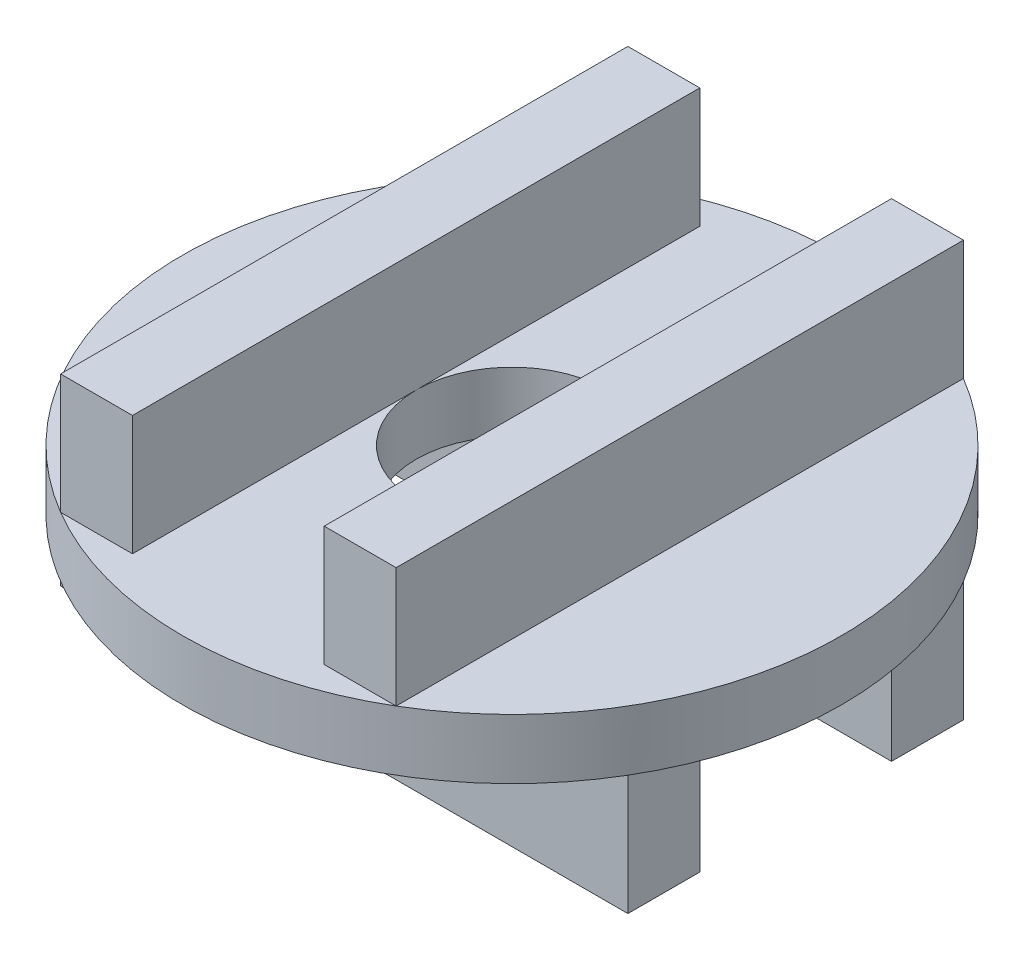
SolidWorks part; units mm, degrees
ref_plane "Front Plane" through (0, 0, 0) normal (0, 0, 1) x (1, 0, 0)
ref_plane "Top Plane" through (0, 0, 0) normal (0, 1, 0) x (1, 0, 0)
ref_plane "Right Plane" through (0, 0, 0) normal (1, 0, 0) x (0, 0, -1)
sketch "Sketch1" plane through (0, 0, 0) normal (0, 1, 0) x (1, 0, 0)
  circle A0 centre (0, 0) radius 55
  circle A1 centre (0, 0) radius 16
  dimension "D1" = 110
  dimension "D2" = 32
extrude "Boss-Extrude1" add sketch "Sketch1" along normal blind 10
sketch "Sketch2" plane through (0, 10, 0) normal (0, 1, 0) x (1, 0, 0)
  line L0 (0, -5.5) -> (0, 5.5) construction
  line L1 (28, 47.3392) -> (16, 47.3392)
  line L2 (28, 47.3392) -> (28, -47.3392)
  line L3 (28, -47.3392) -> (16, -47.3392)
  line L4 (16, 47.3392) -> (16, -47.3392)
  line L5 (-28, -47.3392) -> (-16, -47.3392)
  line L6 (-16, 47.3392) -> (-16, -47.3392)
  line L7 (-28, 47.3392) -> (-16, 47.3392)
  line L8 (-28, 47.3392) -> (-28, -47.3392)
  circle A0 centre (0, 0) radius 55 construction
  circle A1 centre (0, 0) radius 16 construction
  point P6 (0, 0)
  point P7 (0, 0)
  dimension "D1" = 12
extrude "Boss-Extrude2" add sketch "Sketch2" along normal blind 20
sketch "Sketch4" plane through (0, 0, 0) normal (0, -1, 0) x (1, 0, 0)
  line L0 (16.5, 0) -> (-16.5, 0) construction
  line L1 (-47.3392, 28) -> (47.3392, 28)
  line L2 (-47.3392, 28) -> (-47.3392, 16)
  line L3 (-47.3392, 16) -> (47.3392, 16)
  line L4 (47.3392, 28) -> (47.3392, 16)
  line L5 (-47.3392, -16) -> (47.3392, -16)
  line L6 (47.3392, -28) -> (47.3392, -16)
  line L7 (-47.3392, -28) -> (47.3392, -28)
  line L8 (-47.3392, -28) -> (-47.3392, -16)
  circle A0 centre (0, 0) radius 55 construction
  circle A1 centre (0, 0) radius 16 construction
  point P6 (0, 0)
  point P7 (0, 0)
  dimension "D1" = 12
extrude "Boss-Extrude3" add sketch "Sketch4" along normal blind 20
